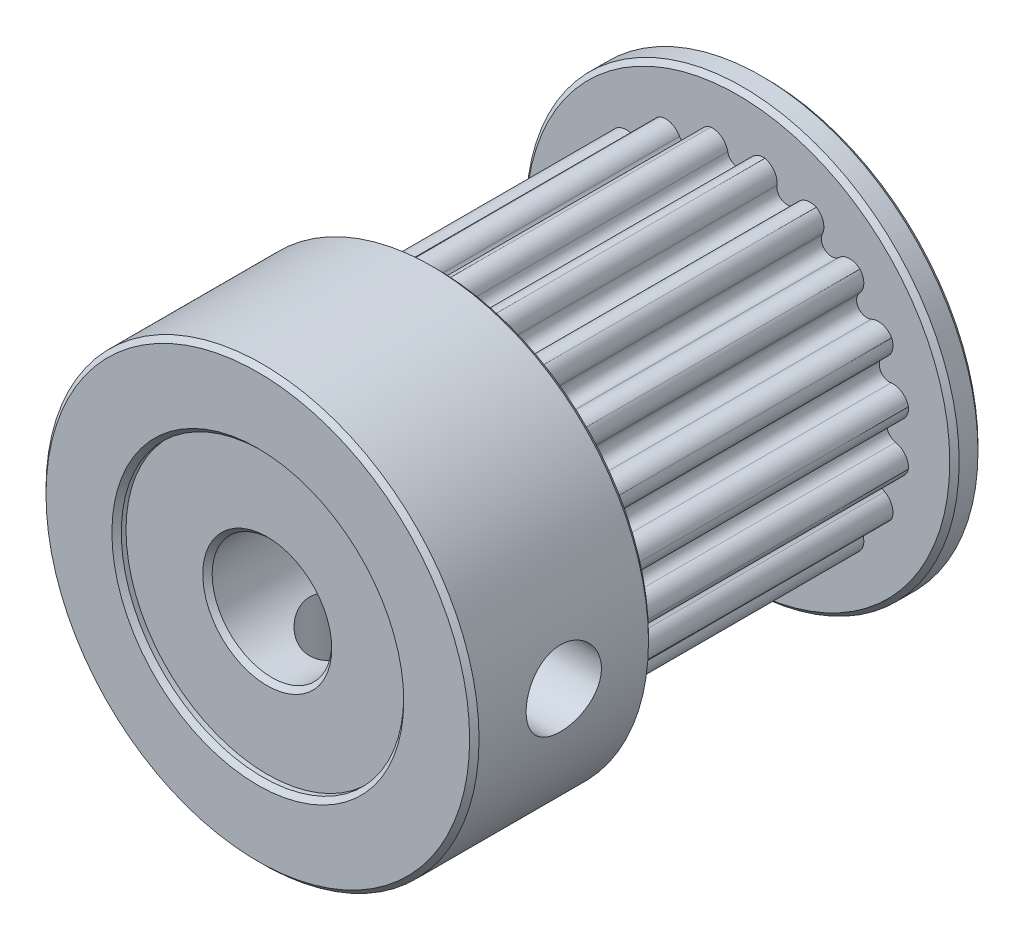
SolidWorks part; units mm, degrees
ref_plane "Plan de face" through (0, 0, 0) normal (0, 0, 1) x (1, 0, 0)
ref_plane "Plan de dessus" through (0, 0, 0) normal (0, 1, 0) x (1, 0, 0)
ref_plane "Plan de droite" through (0, 0, 0) normal (1, 0, 0) x (0, 0, -1)
sketch "Esquisse1" plane through (0, 0, 0) normal (0, 0, 1) x (1, 0, 0)
  circle A0 centre (0, 0) radius 11.5
  circle A1 centre (0, 0) radius 3.175
  dimension "D1" = 23
  dimension "D2" = 6.35
extrude "Boss.-Extru.1" add sketch "Esquisse1" along normal blind 27
ref_plane "Plan1" through (0, 0, 1.5) normal (0, 0, -1) x (-1, 0, 0)
sketch "Esquisse2" plane through (0, 0, 1.5) normal (0, 0, -1) x (-1, 0, 0)
  circle A0 centre (0, 0) radius 9.17
  circle A1 centre (0, 0) radius 11.5
  dimension "D1" = 18.34
extrude "Enlèv. mat.-Extru.1" cut sketch "Esquisse2" against normal blind 16
sketch "Esquisse3" plane through (0, 0, 17.5) normal (0, 0, -1) x (-1, 0, 0)
  line L0 (-10.9902, 9.17) -> (15.4189, 9.17) construction
  line L1 (0, 0) -> (0, 15.6348) construction
  line L2 (-1.0417, 7.92) -> (1.5586, 7.92) construction
  circle A0 centre (0, 0) radius 9.17 construction
  circle A1 centre (0, 0) radius 9.17 construction
  arc A2 (-1.5, 9.0465) -> (-0.5411, 8.3716) centre (-1.3633, 8.2221) cw
  arc A3 (-0.5411, 8.3716) -> (0.5411, 8.3716) centre (0, 8.47) ccw
  arc A4 (0.5411, 8.3716) -> (1.5, 9.0465) centre (1.3633, 8.2221) cw
  arc A5 (-1.5, 9.0465) -> (1.5, 9.0465) centre (0, 0) cw
  point P17 (0, 0)
  dimension "D2" = 0.55
  dimension "D1" = 1.25
  dimension "D3" = 3
extrude "Enlèv. mat.-Extru.2" cut sketch "Esquisse3" along normal up to surface (16 mm away) up to face at (-9.17, 0, 1.5)
pattern_circular "Répétition circulaire1" count 20 over 360 about axis through (0, 0, 0) along (0, 0, 1) of "Enlèv. mat.-Extru.2"
sketch "Esquisse4" plane through (0, 0, 0) normal (0, 1, 0) x (1, 0, 0)
  line L0 (0, 0) -> (0, -26.9226) construction
  line L3 (-11.5, -17.5) -> (17.9359, -17.5) construction
  line L4 (17.9359, -17.5) -> (17.9359, -27) construction
  line L5 (17.9359, -27) -> (-11.5, -27) construction
  line L6 (-11.5, -27) -> (11.5, -27) construction
  line L7 (0, -22.25) -> (29.4359, -22.25) construction
  circle A0 centre (0, -22.25) radius 2
  dimension "D1" = 4
extrude "Enlèv. mat.-Extru.3" cut sketch "Esquisse4" against normal blind 16
pattern_circular "Répétition circulaire2" count 2 over 90 about axis through (0, 0, 27) along (0, 0, -1) of "Enlèv. mat.-Extru.3"
sketch "Esquisse5" plane through (0, 0, 0) normal (0, 0, -1) x (-1, 0, 0)
  circle A0 centre (0, 0) radius 7.5
  dimension "D1" = 15
extrude "Enlèv. mat.-Extru.4" cut sketch "Esquisse5" against normal blind 0.5
ref_plane "Plan2" through (0, 0, 13.5) normal (0, 0, -1) x (-1, 0, 0)
mirror "Symétrie1" about plane through (0, 0, 13.5) normal (0, 0, -1) of "Enlèv. mat.-Extru.4"
chamfer "Chanfrein1" distance 0.25 angle 45 8 edges at (3.175, 0, 26.5) (-3.175, 0, 0.5) (-7.5, 0, 0) (11.5, 0, 0) (11.5, 0, 27) (-11.5, 0, 17.5) (-11.5, 0, 1.5) (-7.5, 0, 27)
